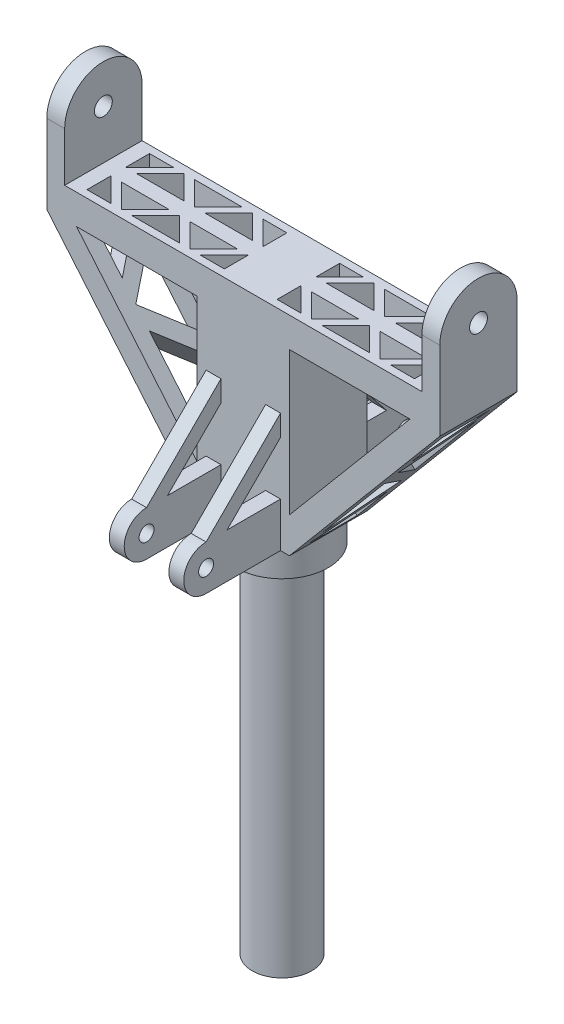
SolidWorks part; units mm, degrees
ref_plane "Front Plane" through (0, 0, 0) normal (0, 0, 1) x (1, 0, 0)
ref_plane "Top Plane" through (0, 0, 0) normal (0, 1, 0) x (1, 0, 0)
ref_plane "Right Plane" through (0, 0, 0) normal (1, 0, 0) x (0, 0, -1)
sketch "Sketch27" plane through (0, 0, 0) normal (0, 0, 1) x (1, 0, 0)
  line L0 (66, 0) -> (-66, 0)
  line L1 (-66, 0) -> (-66, 100)
  line L2 (-66, 100) -> (-60, 100)
  line L3 (-60, 100) -> (-60, 70)
  line L4 (-60, 70) -> (60, 70)
  line L5 (0, 0) -> (0, 82.1741) construction
  line L6 (60, 100) -> (60, 70)
  line L7 (66, 100) -> (60, 100)
  line L8 (66, 0) -> (66, 100)
  point P10 (0, 0)
  point P11 (0, 70)
  dimension "D1" = 120
  dimension "D2" = 6
  dimension "D3" = 100
  dimension "D4" = 30
extrude "Tykkelse leddfester og bredde/høyde selve modellen" add sketch "Sketch27" along normal mid plane 26
sketch "Sketch28" plane through (0, 0, 0) normal (0, -1, 0) x (1, 0, 0)
  line L0 (-66, -13) -> (66, -13) construction
  line L1 (66, 13) -> (66, -13) construction
  circle A1 centre (0, 0) radius 10.5
  circle A2 centre (0, 0) radius 15.5
  point P6 (0, -13)
  point P9 (66, 0)
  dimension "D1" = 21
  dimension "D2" = 5
extrude "Hull til lårben/karbonfiberrør" add sketch "Sketch28" along normal blind 10
sketch "Sketch29" plane through (66, 0, 0) normal (1, 0, 0) x (0, 0, -1)
  line L0 (-13, 100) -> (13, 100) construction
  line L1 (-13, 86.5) -> (-13, 71.5)
  line L2 (13, 86.5) -> (13, 71.5)
  line L4 (-14, 101) -> (0, 101)
  line L8 (0, 86.5) -> (0, 83.5) construction
  line L9 (0, 100) -> (0, 99.5) construction
  line L13 (-13, 71.5) -> (-14, 71.5)
  line L14 (-14, 71.5) -> (-14, 101)
  line L18 (13, 71.5) -> (14, 71.5)
  line L19 (14, 71.5) -> (14, 101)
  line L20 (14, 101) -> (0, 101)
  circle A0 centre (0, 86.5) radius 3
  arc A1 (13, 86.5) -> (-13, 86.5) centre (0, 86.5) ccw
  circle A2 centre (0, 86.5) radius 13 construction
  point P4 (0, 100)
  point P14 (-7, 101)
  dimension "D1" = 6
  dimension "D3" = 15
  dimension "D4" = 0.5
  dimension "D5" = 1
  dimension "D6" = 1
  dimension "D2" = 10
extrude "Skruehull leddfester" cut sketch "Sketch29" against normal through all both and the other way through all
sketch "Fasong (mønster på selve kroppen)" plane through (0, 0, 13) normal (0, 0, 1) x (1, 0, 0)
  line L0 (-66, 60) -> (-15.5, 0)
  line L1 (-66, 86.5) -> (-66, 0) construction
  line L2 (-15.5, 0) -> (-66, 0)
  line L3 (-66, 0) -> (-66, 60)
  line L4 (-60, 70) -> (-66, 70) construction
  line L5 (0, 0) -> (0, 49.2612) construction
  line L6 (15.5, 0) -> (66, 0)
  line L7 (66, 60) -> (15.5, 0)
  line L8 (66, 0) -> (66, 60)
  line L9 (-15.5, 0) -> (-15.5, 60) construction
  line L11 (15.5, 0) -> (15.5, 60) construction
  line L12 (-66, 60) -> (-56, 60) construction
  line L13 (-56, 60) -> (-15.5, 11.8812)
  line L14 (-56, 60) -> (-15.5, 60)
  line L15 (-15.5, 60) -> (-15.5, 11.8812)
  line L16 (56, 60) -> (15.5, 60)
  line L17 (56, 60) -> (15.5, 11.8812)
  line L18 (15.5, 60) -> (15.5, 11.8812)
  dimension "D1" = 10
  dimension "D2" = 10
  dimension "D3" = 31
sketch "Sketch33" plane through (0, 0, -13) normal (0, 0, -1) x (-1, 0, 0)
  line L4 (8.441, 0) -> (-8.441, 0) construction
  line L5 (-3.5, 20) -> (-3.5, 0)
  line L6 (-3.5, 0) -> (-8.5, 0)
  line L7 (-8.5, 0) -> (-8.5, 20)
  line L8 (-8.5, 20) -> (-3.5, 20)
  line L9 (0, 0) -> (0, 33.6157) construction
  line L10 (0, 0) -> (0, 49.2612) construction
  line L11 (8.5, 0) -> (8.5, 20)
  line L12 (3.5, 0) -> (8.5, 0)
  line L13 (3.5, 20) -> (3.5, 0)
  line L14 (8.5, 20) -> (3.5, 20)
  dimension "D1" = 5
  dimension "D2" = 20
  dimension "D3" = 7
extrude "Bredde og avstand stempelende" add sketch "Sketch33" along normal blind 60
sketch "Rod-ende, justere lengden (altså feste til største sylinder)" plane through (8.5, 0, 0) normal (1, 0, 0) x (0, 0, -1)
  line L0 (13, 20) -> (13, 0) construction
  line L5 (43, -1) -> (74, -1)
  line L6 (74, -1) -> (74, 21)
  line L7 (74, 21) -> (43, 21)
  line L9 (73, 0) -> (13, 0) construction
  line L11 (73, 20) -> (73, 0) construction
  line L12 (73, 20) -> (13, 20) construction
  line L13 (33, 1) -> (13, 1)
  line L14 (13, 0) -> (13, 86.5) construction
  line L15 (13, 1) -> (13, -1)
  line L16 (13, -1) -> (43, -1)
  line L17 (43, 21) -> (13, 21)
  line L18 (13, 21) -> (13, 19)
  line L19 (13, 19) -> (33, 19)
  circle A0 centre (33, 10) radius 3
  arc A1 (33, 1) -> (33, 19) centre (33, 10) ccw
  circle A2 centre (33, 10) radius 9 construction
  point P6 (13, 10)
  dimension "D1" = 6
  dimension "D3" = 20
  dimension "D4" = 1
  dimension "D5" = 1
  dimension "D6" = 1
  dimension "D2" = 6
sketch "Sketch39" plane through (0, 0, 13) normal (0, 0, 1) x (1, 0, 0)
  line L1 (-7.5, 0) -> (-7.5, 15)
  line L3 (-7.5, 15) -> (-12.5, 15)
  line L4 (-12.5, 15) -> (-12.5, 0)
  line L5 (-12.5, 0) -> (-7.5, 0)
  line L11 (0, 0) -> (0, 49.2612) construction
  line L12 (0, 0) -> (0, 21.5969) construction
  line L13 (12.5, 0) -> (7.5, 0)
  line L14 (12.5, 15) -> (12.5, 0)
  line L15 (7.5, 15) -> (12.5, 15)
  line L16 (7.5, 0) -> (7.5, 15)
  line L17 (-8.441, 0) -> (8.441, 0) construction
  dimension "D1" = 15
  dimension "D2" = 5
  dimension "D3" = 7.5
extrude "Cut-Extrude4" cut sketch "Fasong (mønster på selve kroppen)" against normal through all
sketch "Sketch40" plane through (-9.0728, -7.6363, 0) normal (-0.7651, -0.6439, 0) x (0, 0, 1)
  line L0 (0, 88.4046) -> (0, 35.3376) construction
  line L1 (-13, 88.4046) -> (13, 88.4046) construction
  line L2 (-8, 81.9046) -> (8, 81.9046)
  line L3 (-13, 9.9811) -> (-13, 88.4046) construction
  line L4 (-8, 81.9046) -> (8, 65.9046)
  line L6 (-8, 74.8335) -> (8, 58.8335)
  line L8 (-8, 42.8335) -> (8, 58.8335)
  line L9 (8, 81.9046) -> (8, 65.9046)
  line L10 (-8, 42.8335) -> (-8, 74.8335)
  line L13 (8, 19.7625) -> (-8, 35.7625)
  line L16 (8, 51.7625) -> (-8, 35.7625)
  line L18 (8, 19.7625) -> (8, 51.7625)
  line L19 (-8, 28.6914) -> (8, 12.6914)
  line L20 (8, 12.6914) -> (-8, 12.6914)
  line L21 (-8, 12.6914) -> (-8, 28.6914)
  line L22 (-13, 9.9811) -> (0, 9.9811) construction
  point P8 (0, 81.9046)
  dimension "D1" = 6.5
  dimension "D2" = 5
  dimension "D3" = 45
  dimension "D4" = 90
  dimension "D5" = 5
  dimension "D6" = 5
  dimension "D7" = 90
  dimension "D8" = 5
  dimension "D9" = 2.7103
extrude "Sidemønster" cut sketch "Sketch40" against normal up to vertex (7.6508 mm away)
sketch "Sketch42" plane through (9.0728, -7.6363, 0) normal (0.7651, -0.6439, 0) x (0, 0, -1)
  line L3 (0, 88.4046) -> (0, 81.9046) construction
  line L4 (13, 88.4046) -> (-13, 88.4046) construction
  line L5 (8, 81.9046) -> (-8, 81.9046)
  line L6 (-13, 88.4046) -> (-13, 9.9811) construction
  line L7 (-8, 81.9046) -> (-8, 65.9046)
  line L8 (-8, 65.9046) -> (8, 81.9046)
  line L9 (8, 74.8335) -> (-8, 58.8335)
  line L11 (8, 42.8335) -> (8, 74.8335)
  line L12 (8, 42.8335) -> (-8, 58.8335)
  line L13 (-8, 51.7625) -> (8, 35.7625)
  line L15 (-8, 19.7625) -> (-8, 51.7625)
  line L16 (-8, 19.7625) -> (8, 35.7625)
  line L17 (8, 28.6914) -> (-8, 12.6914)
  line L18 (-8, 12.6914) -> (8, 12.6914)
  line L19 (8, 12.6914) -> (8, 28.6914)
  point P8 (0, 88.4046)
  point P11 (0, 81.9046)
  dimension "D1" = 6.5
  dimension "D2" = 5
  dimension "D3" = 45
  dimension "D4" = 5
  dimension "D5" = 45
  dimension "D6" = 45
  dimension "D7" = 5
  dimension "D9" = 5
extrude "Sidemønster 2" cut sketch "Sketch42" against normal up to vertex (7.6508 mm away)
sketch "Sketch44" plane through (0, 0, 0) normal (0, -1, 0) x (1, 0, 0)
  circle A0 centre (0, 0) radius 10.5
  dimension "D1" = 21
extrude "Utvidet lårbenhull inn i selve kroppen" cut sketch "Sketch44" against normal blind 40
sketch "Sketch45" plane through (0, 70, 0) normal (0, 1, 0) x (1, 0, 0)
  line L3 (-39.9289, 10.5) -> (-31.9289, 2.5)
  line L5 (-23.9289, 10.5) -> (-39.9289, 10.5)
  line L6 (-16.8579, 10.5) -> (-8.8579, 2.5)
  line L7 (0, 0) -> (0, 11.265) construction
  line L8 (0, 0) -> (-55, 0) construction
  line L9 (-60, -13) -> (-60, 13) construction
  line L10 (-55, 2.5) -> (-55, 10.5)
  line L11 (-55, 10.5) -> (-47, 10.5)
  line L12 (-47, 10.5) -> (-55, 2.5)
  line L13 (60, 13) -> (-60, 13) construction
  line L14 (-43.4645, 10.5) -> (-51.4645, 2.5)
  line L15 (-51.4645, 2.5) -> (-35.4645, 2.5)
  line L17 (-43.4645, 10.5) -> (-35.4645, 2.5)
  line L18 (-23.9289, 10.5) -> (-31.9289, 2.5)
  line L19 (-20.3934, 10.5) -> (-28.3934, 2.5)
  line L20 (-28.3934, 2.5) -> (-12.3934, 2.5)
  line L22 (-20.3934, 10.5) -> (-12.3934, 2.5)
  line L23 (-8.8579, 2.5) -> (-8.8579, 10.5)
  line L24 (-8.8579, 10.5) -> (-16.8579, 10.5)
  line L25 (-8.8579, -2.5) -> (-8.8579, -10.5)
  line L26 (-16.8579, -10.5) -> (-8.8579, -2.5)
  line L27 (-8.8579, -10.5) -> (-16.8579, -10.5)
  line L28 (-20.3934, -10.5) -> (-12.3934, -2.5)
  line L29 (-28.3934, -2.5) -> (-12.3934, -2.5)
  line L30 (-20.3934, -10.5) -> (-28.3934, -2.5)
  line L31 (-23.9289, -10.5) -> (-31.9289, -2.5)
  line L32 (-23.9289, -10.5) -> (-39.9289, -10.5)
  line L33 (-39.9289, -10.5) -> (-31.9289, -2.5)
  line L34 (-43.4645, -10.5) -> (-35.4645, -2.5)
  line L35 (-51.4645, -2.5) -> (-35.4645, -2.5)
  line L36 (-43.4645, -10.5) -> (-51.4645, -2.5)
  line L37 (-55, -10.5) -> (-47, -10.5)
  line L38 (-55, -2.5) -> (-55, -10.5)
  line L39 (-47, -10.5) -> (-55, -2.5)
  line L40 (8.8579, 2.5) -> (8.8579, 10.5)
  line L41 (16.8579, 10.5) -> (8.8579, 2.5)
  line L42 (8.8579, 10.5) -> (16.8579, 10.5)
  line L43 (16.8579, -10.5) -> (8.8579, -2.5)
  line L44 (8.8579, -10.5) -> (16.8579, -10.5)
  line L45 (8.8579, -2.5) -> (8.8579, -10.5)
  line L46 (20.3934, -10.5) -> (28.3934, -2.5)
  line L47 (28.3934, -2.5) -> (12.3934, -2.5)
  line L48 (20.3934, -10.5) -> (12.3934, -2.5)
  line L49 (20.3934, 10.5) -> (12.3934, 2.5)
  line L50 (28.3934, 2.5) -> (12.3934, 2.5)
  line L51 (20.3934, 10.5) -> (28.3934, 2.5)
  line L52 (23.9289, 10.5) -> (31.9289, 2.5)
  line L53 (23.9289, 10.5) -> (39.9289, 10.5)
  line L54 (39.9289, 10.5) -> (31.9289, 2.5)
  line L55 (23.9289, -10.5) -> (39.9289, -10.5)
  line L56 (39.9289, -10.5) -> (31.9289, -2.5)
  line L57 (23.9289, -10.5) -> (31.9289, -2.5)
  line L58 (43.4645, -10.5) -> (51.4645, -2.5)
  line L59 (51.4645, -2.5) -> (35.4645, -2.5)
  line L60 (43.4645, -10.5) -> (35.4645, -2.5)
  line L61 (55, -2.5) -> (55, -10.5)
  line L62 (47, -10.5) -> (55, -2.5)
  line L63 (55, -10.5) -> (47, -10.5)
  line L64 (43.4645, 10.5) -> (35.4645, 2.5)
  line L65 (51.4645, 2.5) -> (35.4645, 2.5)
  line L66 (43.4645, 10.5) -> (51.4645, 2.5)
  line L67 (55, 10.5) -> (47, 10.5)
  line L68 (55, 2.5) -> (55, 10.5)
  line L69 (47, 10.5) -> (55, 2.5)
  dimension "D1" = 5
  dimension "D2" = 2.5
  dimension "D3" = 2.5
  dimension "D4" = 45
  dimension "D5" = 2.5
  dimension "D6" = 45
  dimension "D7" = 2.5
  dimension "D8" = 45
  dimension "D9" = 2.5
  dimension "D10" = 45
  dimension "D11" = 2.5
extrude "Mønster topp" cut sketch "Sketch45" against normal up to vertex (10 mm away)
extrude "Stempelende av største sylinder " cut sketch "Rod-ende, justere lengden (altså feste til største sylinder)" against normal through all both and the other way through all
extrude "Sylinderfeste, selve den lille sylinderen " add sketch "Sketch39" along normal blind 48
sketch "Sketch46" plane through (8.5, 0, 0) normal (1, 0, 0) x (0, 0, -1)
  line L2 (13, 60) -> (13, 0) construction
  line L3 (13, 35.9961) -> (26.5969, 19)
  line L4 (33, 19) -> (13, 19) construction
  line L5 (26.5969, 19) -> (33, 19)
  line L6 (33, 19) -> (13, 44)
  line L7 (13, 44) -> (13, 35.9961)
  line M3 (33, 19) -> (13, 19)
  dimension "D1" = 5
  dimension "D2" = 25
extrude "Støtter største sylinder 1" add sketch "Sketch46" against normal blind 5 contours L6 L7 L3 M3
sketch "Sketch47" plane through (-8.5, 0, 0) normal (-1, 0, 0) x (0, 0, 1)
  line L0 (-33, 19) -> (-13, 44)
  line L1 (-13, 0) -> (-13, 60) construction
  line L2 (-13, 44) -> (-13, 35.9961) construction
  line L3 (-13, 44) -> (-13, 35.9961)
  line L4 (-13, 35.9961) -> (-26.5969, 19)
  line L5 (-13, 19) -> (-33, 19) construction
  line L6 (-13, 35.9961) -> (-26.5969, 19) construction
  line L7 (-26.5969, 19) -> (-33, 19)
extrude "Støtter største sylinder 2" add sketch "Sketch47" against normal blind 5
sketch "Sketch48" plane through (-12.5, 0, 0) normal (-1, 0, 0) x (0, 0, 1)
  line L0 (13, 15) -> (13, 0) construction
  line L1 (38, 0) -> (23.1798, 0)
  line L2 (23.1798, 0) -> (23.1798, -1)
  line L3 (23.1798, -1) -> (62, -1)
  line L4 (62, -1) -> (62, 16)
  line L5 (62, 16) -> (13, 16)
  line L6 (13, 0) -> (13, 60) construction
  line L7 (13, 16) -> (13, 15)
  line L8 (13, 15) -> (38, 15)
  line L9 (61, 15) -> (13, 15) construction
  line L10 (61, 15) -> (61, 0) construction
  circle A0 centre (38, 7.5) radius 2.5
  arc A1 (38, 0) -> (38, 15) centre (38, 7.5) ccw
  circle A2 centre (38, 7.5) radius 7.5 construction
  point P6 (13, 7.5)
  dimension "D1" = 5
  dimension "D3" = 1
  dimension "D4" = 1
  dimension "D5" = 1
  dimension "D6" = 25
  dimension "D2" = 5
extrude "Sylinderfeste, liten sylinder" cut sketch "Sketch48" against normal through all both and the other way through all
sketch "Sketch49" plane through (-12.5, 0, 0) normal (-1, 0, 0) x (0, 0, 1)
  line L0 (38, 15) -> (13, 40)
  line L1 (13, 0) -> (13, 60) construction
  line L2 (13, 40) -> (13, 32.9289)
  line L3 (30.9289, 15) -> (38, 15)
  line L4 (13, 32.9289) -> (30.9289, 15)
  dimension "D1" = 25
  dimension "D2" = 5
sketch "Sketch50" plane through (12.5, 0, 0) normal (1, 0, 0) x (0, 0, -1)
  line L0 (-38, 15) -> (-30.9289, 15)
  line L1 (-30.9289, 15) -> (-13, 32.9289)
  line L2 (-13, 32.9289) -> (-13, 40)
  line L3 (-13, 40) -> (-38, 15)
extrude "Boss-Extrude11" add sketch "Sketch49" against normal blind 5
extrude "Boss-Extrude12" add sketch "Sketch50" against normal blind 5 contours L3 L0 L1 L2
sketch "Sketch51" plane through (0, 40, 0) normal (0, -1, 0) x (1, 0, 0)
  circle A0 centre (0, 0) radius 10
  dimension "D1" = 20
extrude "TIL ASSEMBLY - SLETT FØR PRINTING" add sketch "Sketch51" along normal blind 170
